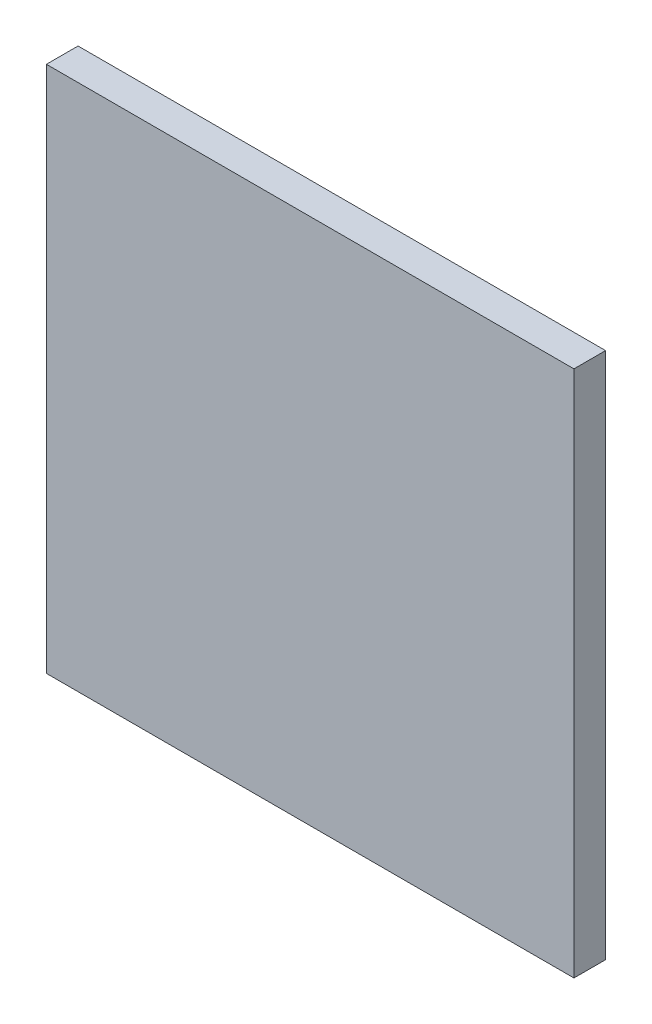
SolidWorks part; units mm, degrees
ref_plane "Alzado" through (0, 0, 0) normal (0, 0, 1) x (1, 0, 0)
ref_plane "Planta" through (0, 0, 0) normal (0, 1, 0) x (1, 0, 0)
ref_plane "Vista lateral" through (0, 0, 0) normal (1, 0, 0) x (0, 0, -1)
sketch "Croquis1" plane through (0, 0, 0) normal (0, 0, 1) x (1, 0, 0)
  line L1 (0, 0) -> (5000, 0)
  line L2 (0, 0) -> (0, 5000)
  line L3 (0, 5000) -> (5000, 5000)
  line L4 (5000, 0) -> (5000, 5000)
  dimension "D1" = 5000
  dimension "D2" = 5000
extrude "Saliente-Extruir1" add sketch "Croquis1" along normal blind 300
